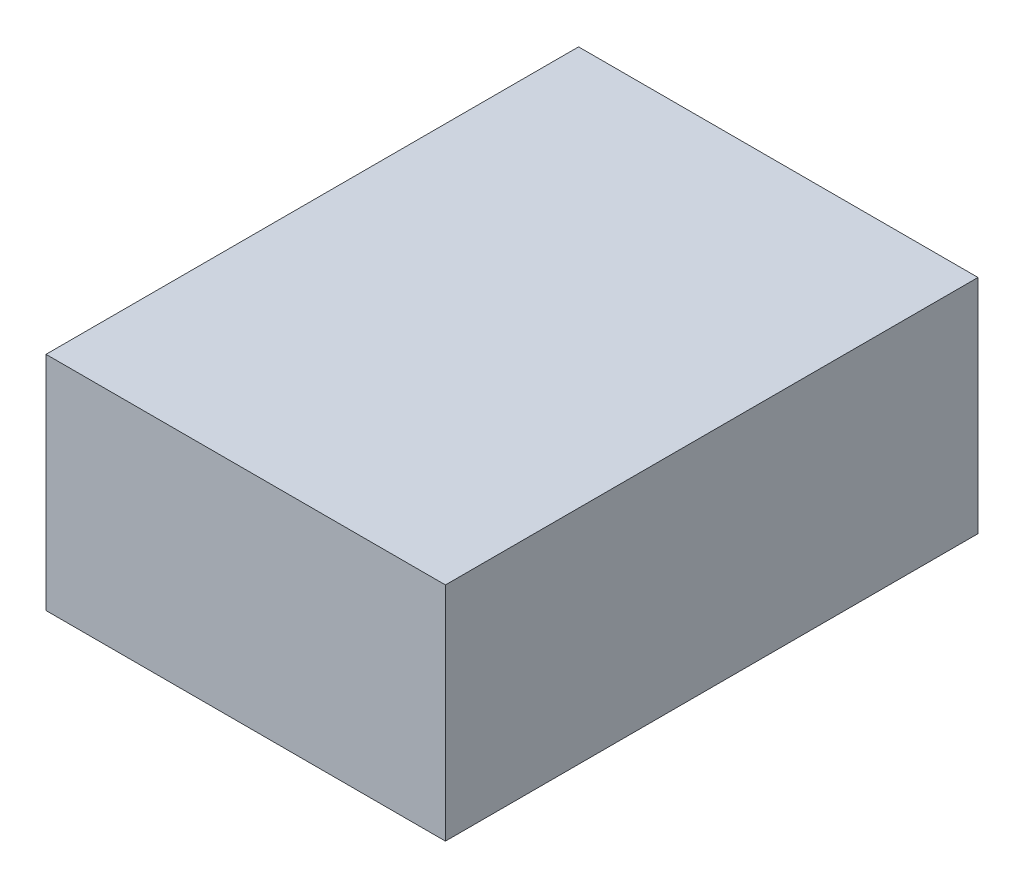
SolidWorks part; units mm, degrees
ref_plane "Спереди" through (0, 0, 0) normal (0, 0, 1) x (1, 0, 0)
ref_plane "Сверху" through (0, 0, 0) normal (0, 1, 0) x (1, 0, 0)
ref_plane "Справа" through (0, 0, 0) normal (1, 0, 0) x (0, 0, -1)
sketch "Эскиз1" plane through (0, 0, 0) normal (0, 0, 1) x (1, 0, 0)
  point P0 (0, 0)
sketch "Эскиз3" plane through (0, 0, 0) normal (0, 0, 1) x (1, 0, 0)
  line L1 (-22.5, -12.5) -> (22.5, -12.5)
  line L2 (-22.5, -12.5) -> (-22.5, 12.5)
  line L3 (-22.5, 12.5) -> (22.5, 12.5)
  line L4 (22.5, -12.5) -> (22.5, 12.5)
  line L5 (-22.5, -12.5) -> (22.5, 12.5) construction
  line L6 (-22.5, 12.5) -> (22.5, -12.5) construction
  point P0 (0, 0)
extrude "Бобышка-Вытянуть2" add sketch "Эскиз3" along normal blind 60
sketch "Эскиз4" plane through (0, 0, 0) normal (0, 0, -1) x (-1, 0, 0)
  line L1 (-21, -11) -> (21, -11)
  line L2 (-21, -11) -> (-21, 11)
  line L3 (-21, 11) -> (21, 11)
  line L4 (21, -11) -> (21, 11)
  line L5 (-21, -11) -> (21, 11) construction
  line L6 (-21, 11) -> (21, -11) construction
  point P0 (0, 0)
extrude "Вырез-Вытянуть1" cut sketch "Эскиз4" against normal blind 11
